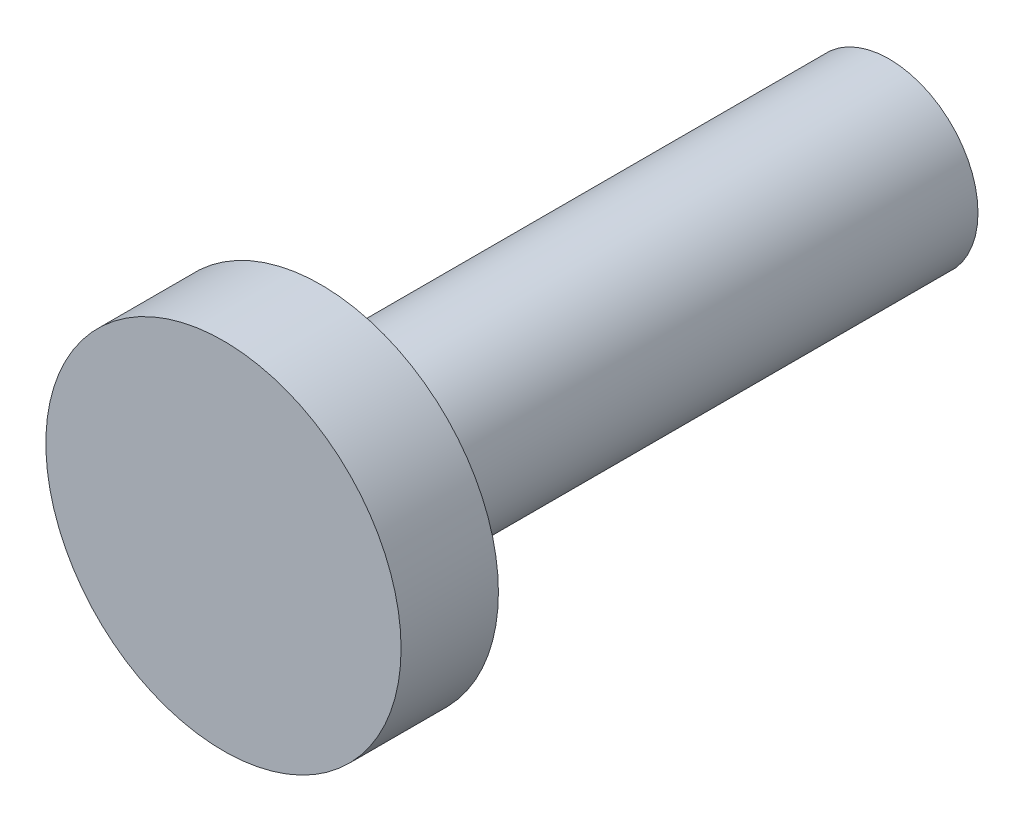
SolidWorks part; units mm, degrees
ref_plane "Plan de face" through (0, 0, 0) normal (0, 0, 1) x (1, 0, 0)
ref_plane "Plan de dessus" through (0, 0, 0) normal (0, 1, 0) x (1, 0, 0)
ref_plane "Plan de droite" through (0, 0, 0) normal (1, 0, 0) x (0, 0, -1)
sketch "Esquisse1" plane through (0, 0, 0) normal (0, 0, 1) x (1, 0, 0)
  circle A0 centre (0, 0) radius 2.5
  dimension "D1" = 5
extrude "Boss.-Extru.1" add sketch "Esquisse1" along normal blind 1.37
sketch "Esquisse2" plane through (0, 0, 0) normal (0, 0, -1) x (-1, 0, 0)
  circle A0 centre (0, 0) radius 1.25
  dimension "D1" = 2.5
extrude "Boss.-Extru.2" add sketch "Esquisse2" along normal blind 8
